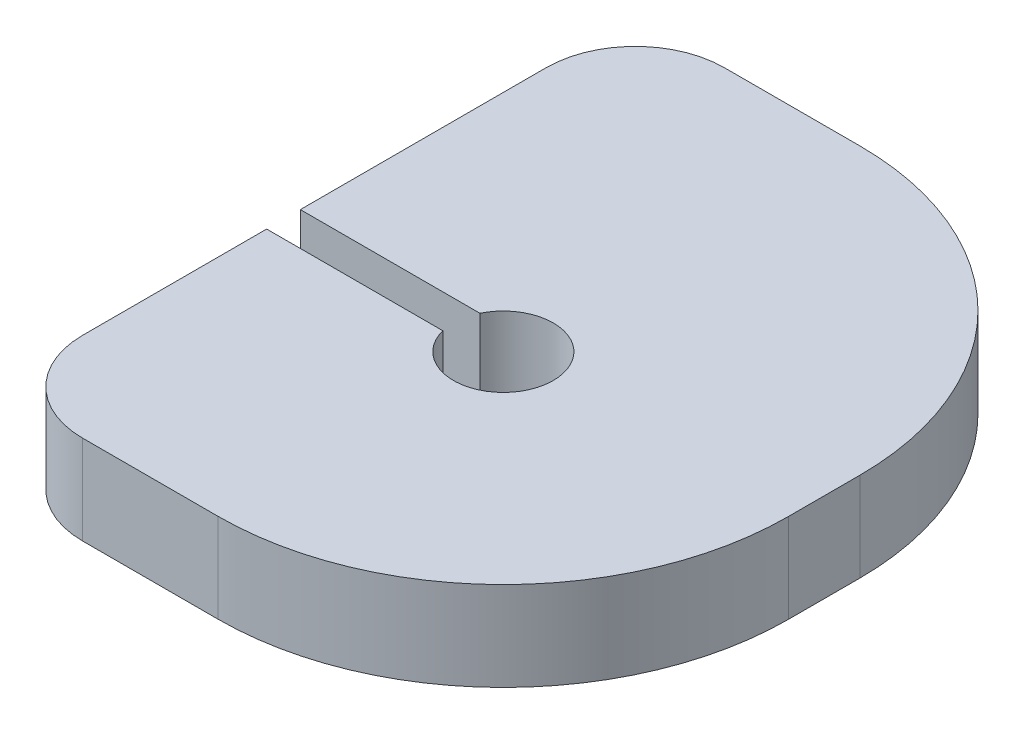
SolidWorks part; units mm, degrees
ref_plane "Front Plane" through (0, 0, 0) normal (0, 0, 1) x (1, 0, 0)
ref_plane "Top Plane" through (0, 0, 0) normal (0, 1, 0) x (1, 0, 0)
ref_plane "Right Plane" through (0, 0, 0) normal (1, 0, 0) x (0, 0, -1)
sketch "Sketch1" plane through (0, 0, 0) normal (0, 1, 0) x (1, 0, 0)
  line L1 (-25.4, 11.43) -> (25.4, 11.43)
  line L2 (-25.4, 11.43) -> (-25.4, -11.43)
  line L3 (-25.4, -11.43) -> (25.4, -11.43)
  line L4 (25.4, 11.43) -> (25.4, -11.43)
  dimension "D1" = 22.86
  dimension "D2" = 50.8
  dimension "D3" = 11.43
  dimension "D4" = 25.4
extrude "Boss-Extrude1" add sketch "Sketch1" along normal blind 3.175
fillet "Fillet1" radius 10.16 2 edges at (-25.4, 1.5875, 11.43) (25.4, 1.5875, 11.43)
sketch "Sketch3" plane through (0, 3.175, 0) normal (0, 1, 0) x (1, 0, 0)
  line L0 (-7.7526, -1.27) -> (18.5521, -1.27) construction
  circle A0 centre (15.24, -1.27) radius 1.778
  arc A2 (15.24, -11.43) -> (25.4, -1.27) centre (15.24, -1.27) ccw construction
  circle A3 centre (-3.81, -1.27) radius 1.778
  dimension "D1" = 3.556
  dimension "D6" = 3.556
  dimension "D5" = 19.05
extrude "Cut-Extrude1" cut sketch "Sketch3" against normal through all
fillet "Fillet3" radius 10.16 2 edges at (-25.4, 1.5875, -11.43) (25.4, 1.5875, -11.43)
sketch "Sketch4" plane through (0, 3.175, 0) normal (0, 1, 0) x (1, 0, 0)
  line L0 (7.239, 11.43) -> (7.239, -11.43)
  line L1 (-25.4, 1.27) -> (-25.4, -1.27) construction
  line L2 (7.239, 11.43) -> (-25.4, 11.43)
  line L5 (15.24, 11.43) -> (-15.24, 11.43) construction
  line L7 (-15.24, -11.43) -> (15.24, -11.43) construction
  line L9 (7.239, -11.43) -> (-25.4, -11.43)
  line L10 (-25.4, 11.43) -> (-25.4, -11.43)
  dimension "D1" = 18.161
extrude "Cut-Extrude2" cut sketch "Sketch4" against normal through all
fillet "Fillet9" radius 3.175 2 edges at (7.239, 1.5875, 11.43) (7.239, 1.5875, -11.43)
sketch "Sketch5" plane through (0, 3.175, 0) normal (0, 1, 0) x (1, 0, 0)
  line L0 (7.239, -8.255) -> (7.239, 8.255) construction
  line L1 (7.239, -0.5009) -> (14.039, -0.5009)
  line L2 (7.239, -0.5009) -> (7.239, -1.7009)
  line L3 (7.239, -1.7009) -> (14.039, -1.7009)
  line L4 (14.039, -0.5009) -> (14.039, -1.7009)
  line L5 (14.039, -0.5009) -> (7.039, -0.5009) construction
  line L6 (14.039, -1.7009) -> (7.039, -1.7009) construction
  line L10 (14.039, -4.8509) -> (14.039, 2.6491) construction
extrude "Cut-Extrude4" cut sketch "Sketch5" against normal through all contours L4 L3 L2 L1
equation "\"D4@Sketch1\"=\"D2@Sketch1\"/2"
equation "\"D3@Sketch1\"=\"D1@Sketch1\"/2"
